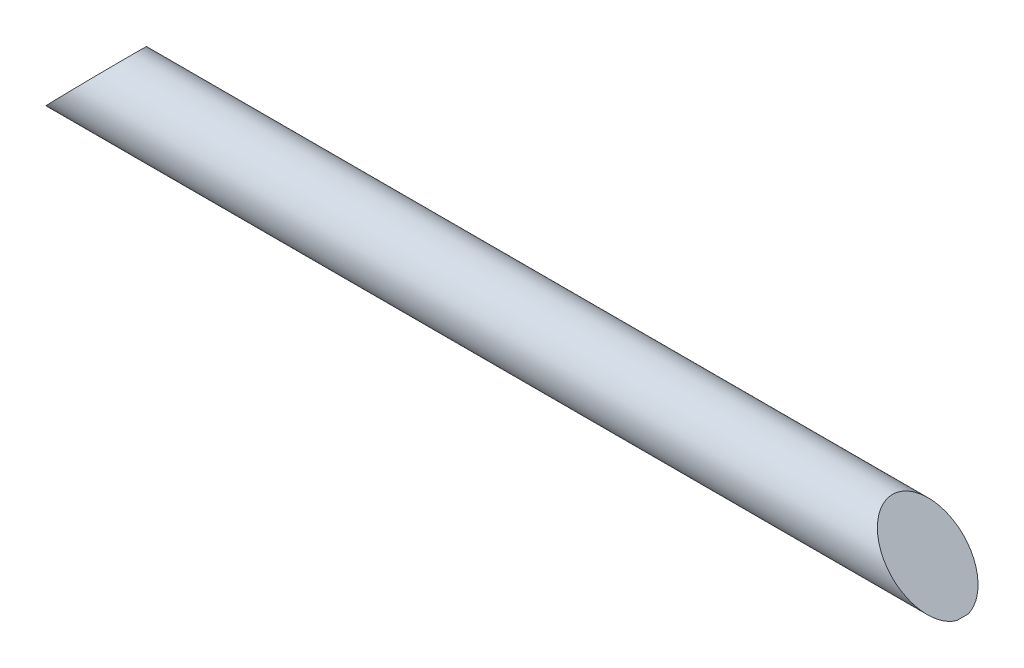
SolidWorks part; units mm, degrees
ref_plane "Front Plane" through (0, 0, 0) normal (0, 0, 1) x (1, 0, 0)
ref_plane "Top Plane" through (0, 0, 0) normal (0, 1, 0) x (1, 0, 0)
ref_plane "Right Plane" through (0, 0, 0) normal (1, 0, 0) x (0, 0, -1)
sketch "Sketch2" plane through (0, 0, 0) normal (0, 1, 0) x (1, 0, 0)
  line L0 (0, 0) -> (1600, 0)
  line L1 (1600, 0) -> (1600, 63.75)
  line L2 (1600, 63.75) -> (0, 63.75)
  line L3 (0, 63.75) -> (0, 0)
revolve "Revolve1" add sketch "Sketch2" angle 360 about L2
sketch "Sketch3" plane through (0, 0, 0) normal (0, 0, 1) x (1, 0, 0)
  line L1 (0, -63.75) -> (1600, -63.75) construction
  line L2 (125, -63.75) -> (125, -66.8586)
  line L4 (1600, 63.75) -> (0, 63.75) construction
  line L5 (125, 63.75) -> (0, -63.75)
  line L8 (1475, 63.75) -> (1600, -63.75)
  line L9 (0, -63.75) -> (0, 63.75)
  line L10 (0, 63.75) -> (125, 63.75)
  line L11 (1475, 63.75) -> (1600, 63.75)
  line L12 (1600, 63.75) -> (1600, -63.75)
extrude "Cut-Extrude2" cut sketch "Sketch3" against normal through all both and the other way through all contours L10 L9 L5 | L12 L11 L8
sketch "Sketch5" plane through (0, 0, 0) normal (1, 0, 0) x (0, 0, -1)
  line L0 (63.75, -63.75) -> (0, -63.75)
  line L1 (0, -63.75) -> (0, -62.9623)
  line L2 (0, -62.9623) -> (127.5, -62.9623)
  line L3 (127.5, -62.9623) -> (127.5, -63.75)
  line L4 (127.5, -63.75) -> (63.75, -63.75)
  circle A0 centre (63.75, 0) radius 63.75 construction
extrude "Cut-Extrude3" cut sketch "Sketch5" along normal through all
sketch "Sketch7" plane through (0, -62.9623, 0) normal (0, -1, 0) x (1, 0, 0)
  line L0 (1599.2278, -73.7404) -> (1599.2278, -53.7596)
